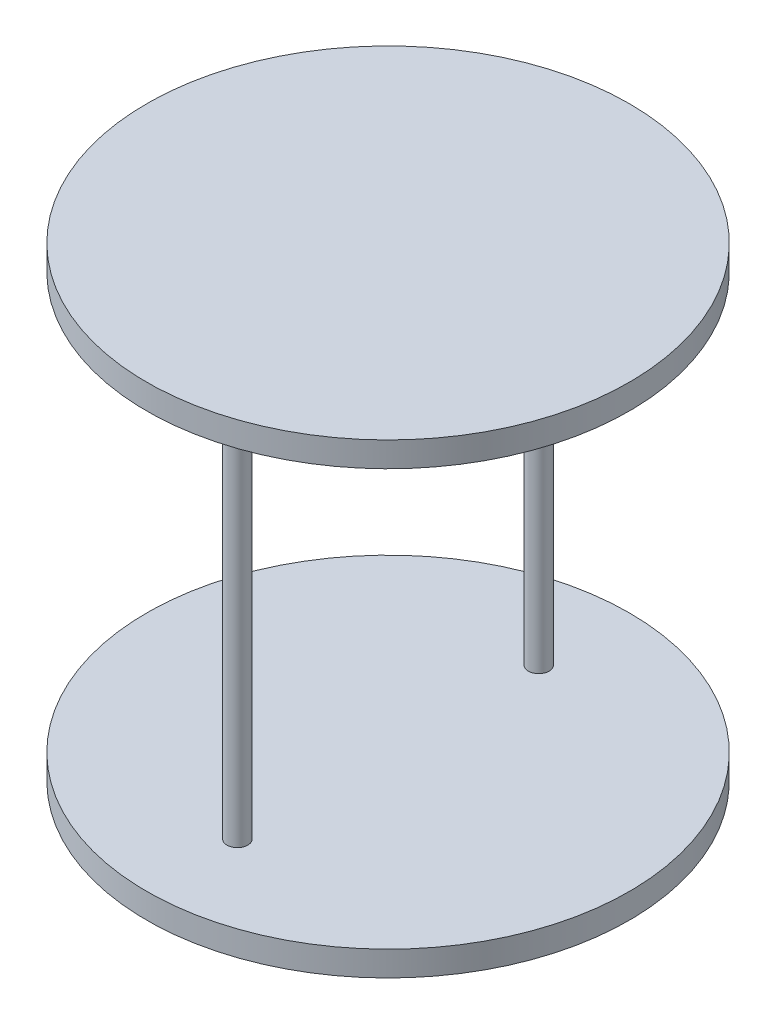
SolidWorks part; units mm, degrees
ref_plane "Front Plane" through (0, 0, 0) normal (0, 0, 1) x (1, 0, 0)
ref_plane "Top Plane" through (0, 0, 0) normal (0, 1, 0) x (1, 0, 0)
ref_plane "Right Plane" through (0, 0, 0) normal (1, 0, 0) x (0, 0, -1)
sketch "Sketch1" plane through (0, 0, 0) normal (0, 1, 0) x (1, 0, 0)
  circle A0 centre (0, 0) radius 73.66
  dimension "D1" = 147.32
extrude "Boss-Extrude1" add sketch "Sketch1" along normal blind 7.62
sketch "Sketch2" plane through (0, 7.62, 0) normal (0, 1, 0) x (1, 0, 0)
  line L0 (0, 0) -> (0, -46)
  line L1 (0, 0) -> (0, 46)
  circle A0 centre (0, 46) radius 3.175
  circle A1 centre (0, -46) radius 3.175
  dimension "D1" = 6.35
  dimension "D2" = 6.35
  dimension "D3" = 46
  dimension "D4" = 46
extrude "Boss-Extrude2" add sketch "Sketch2" along normal blind 63.5
mirror "Mirror1" about plane through (0, 71.12, 0) normal (0, 1, 0) of "Boss-Extrude2"
sketch "Sketch3" plane through (0, 134.62, 0) normal (0, 1, 0) x (1, 0, 0)
  line L0 (0, -46) -> (0, 46) construction
  circle A0 centre (0, 0) radius 73.66
extrude "Boss-Extrude3" add sketch "Sketch3" along normal blind 7.62
